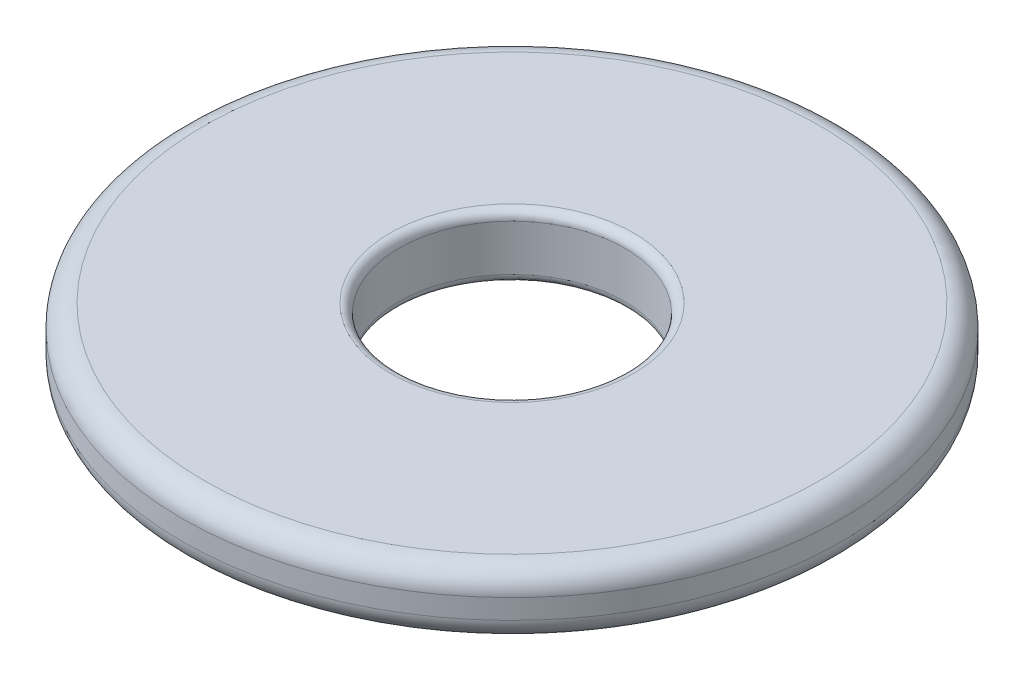
SolidWorks part; units mm, degrees
material "ABS"
ref_plane "Front Plane" through (0, 0, 0) normal (0, 0, 1) x (1, 0, 0)
ref_plane "Top Plane" through (0, 0, 0) normal (0, 1, 0) x (1, 0, 0)
ref_plane "Right Plane" through (0, 0, 0) normal (1, 0, 0) x (0, 0, -1)
sketch "Sketch1" plane through (0, 0, 0) normal (0, 1, 0) x (1, 0, 0)
  circle A0 centre (0, 0) radius 9.525
  circle A1 centre (0, 0) radius 3.2639
  dimension "D1" = 19.05
  dimension "D2" = 6.5278
extrude "Boss-Extrude1" add sketch "Sketch1" along normal blind 1.8415
fillet "Fillet1" radius 0.635 2 edges at (0, 0, 9.525) (0, 1.8415, 9.525)
fillet "Fillet2" radius 0.254 2 edges at (0, 0, 3.2639) (0, 1.8415, 3.2639)
